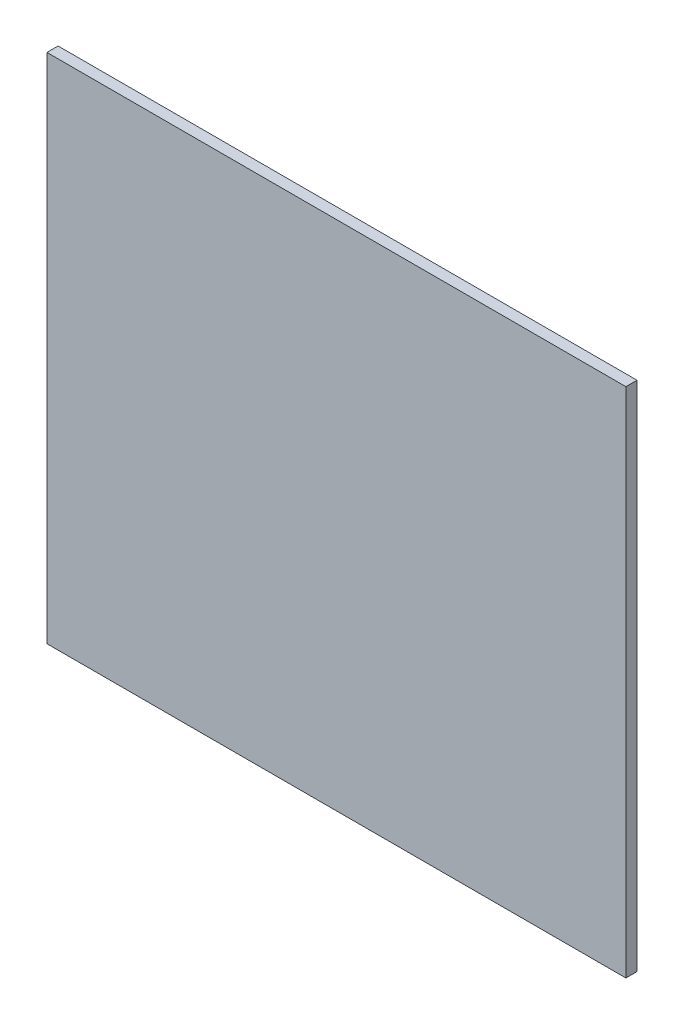
SolidWorks part; units mm, degrees
material "Fundición gris (SN)"
ref_plane "Alzado" through (0, 0, 0) normal (0, 0, 1) x (1, 0, 0)
ref_plane "Planta" through (0, 0, 0) normal (0, 1, 0) x (1, 0, 0)
ref_plane "Vista lateral" through (0, 0, 0) normal (1, 0, 0) x (0, 0, -1)
sketch "Croquis1" plane through (0, 0, 0) normal (0, 0, 1) x (1, 0, 0)
  line L1 (130, -115) -> (-130, -115)
  line L2 (130, -115) -> (130, 115)
  line L3 (130, 115) -> (-130, 115)
  line L4 (-130, -115) -> (-130, 115)
  line L5 (130, -115) -> (-130, 115) construction
  line L6 (130, 115) -> (-130, -115) construction
  point P0 (0, 0)
  dimension "D1" = 230
  dimension "D2" = 260
extrude "Saliente-Extruir1" add sketch "Croquis1" along normal blind 5
